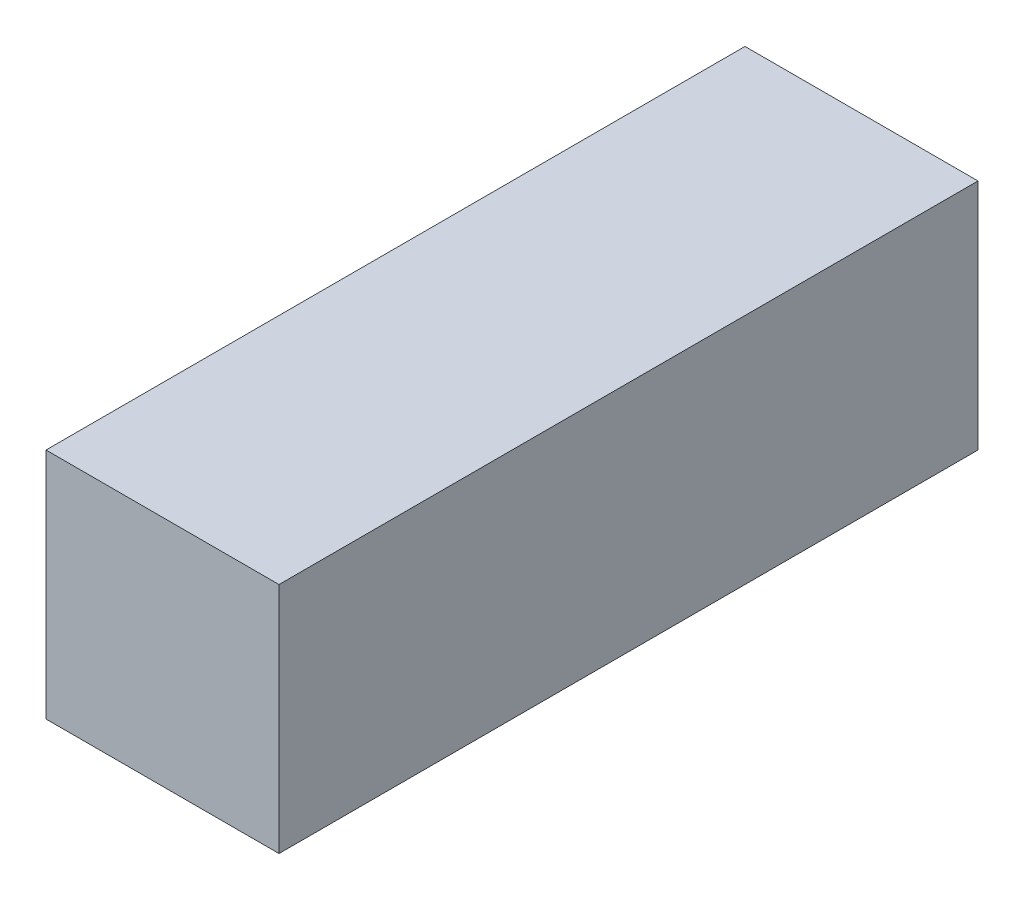
SolidWorks part; units mm, degrees
material "Plain Carbon Steel"
ref_plane "Front Plane" through (0, 0, 0) normal (0, 0, 1) x (1, 0, 0)
ref_plane "Top Plane" through (0, 0, 0) normal (0, 1, 0) x (1, 0, 0)
ref_plane "Right Plane" through (0, 0, 0) normal (1, 0, 0) x (0, 0, -1)
sketch "Sketch1" plane through (0, 0, 0) normal (0, 0, 1) x (1, 0, 0)
  line L1 (2.3813, -2.3813) -> (-2.3813, -2.3813)
  line L2 (2.3813, -2.3813) -> (2.3813, 2.3813)
  line L3 (2.3813, 2.3813) -> (-2.3813, 2.3812)
  line L4 (-2.3813, -2.3813) -> (-2.3813, 2.3812)
  line L5 (2.3813, -2.3813) -> (-2.3813, 2.3812) construction
  line L6 (2.3813, 2.3813) -> (-2.3813, -2.3813) construction
  point P0 (0, 0)
  dimension "D1" = 4.7625
extrude "Boss-Extrude1" add sketch "Sketch1" along normal mid plane 14.2875
